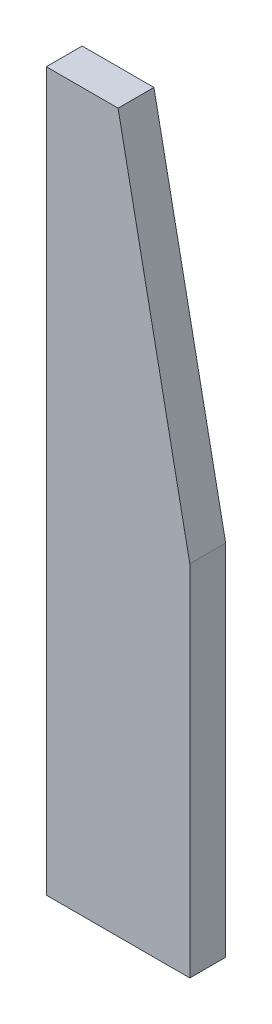
SolidWorks part; units mm, degrees
material "6061 Alloy"
ref_plane "Front Plane" through (0, 0, 0) normal (0, 0, 1) x (1, 0, 0)
ref_plane "Top Plane" through (0, 0, 0) normal (0, 1, 0) x (1, 0, 0)
ref_plane "Right Plane" through (0, 0, 0) normal (1, 0, 0) x (0, 0, -1)
sketch "Sketch1" plane through (0, 0, 0) normal (1, 0, 0) x (0, 0, -1)
  line L1 (-3.175, -63.5) -> (3.175, -63.5)
  line L2 (-3.175, -63.5) -> (-3.175, 63.5)
  line L3 (-3.175, 63.5) -> (3.175, 63.5)
  line L4 (3.175, -63.5) -> (3.175, 63.5)
  line L5 (-3.175, -63.5) -> (3.175, 63.5) construction
  line L6 (-3.175, 63.5) -> (3.175, -63.5) construction
  point P0 (0, 0)
  dimension "D1" = 6.35
  dimension "D2" = 127
extrude "Boss-Extrude1" add sketch "Sketch1" along normal blind 25.4
hole_wizard "M2.5x0.45 Tapped Hole1" positions "Sketch2" profile "Sketch3" tap size "M2.5x0.45" standard "ANSI Metric"
sketch "Sketch2" plane through (0, 0, 0) normal (-1, 0, 0) x (0, 0, 1)
  line L0 (0, -53.5) -> (0, -26.75)
  line L1 (0, -26.75) -> (0, 0)
  line L2 (0, 0) -> (0, 26.75)
  line L3 (0, 26.75) -> (0, 53.5)
  line L5 (-3.175, 63.5) -> (3.175, 63.5) construction
  point P0 (0, 53.5)
  point P2 (0, 26.75)
  point P4 (0, 0)
  point P7 (0, -26.75)
  point P9 (0, -53.5)
  dimension "D1" = 10
sketch "Sketch3" plane through (0, 53.5, 0) normal (0, 1, 0) x (0, 0, 1)
  line L0 (0, 0) -> (0, 6.9659)
  line L1 (0, 6.9659) -> (1.025, 6.35)
  line L2 (1.025, 6.35) -> (1.025, 0)
  line L5 (1.025, 0) -> (0, 0)
  line L10 (0, 6.9659) -> (-1.025, 6.35) construction
  line L11 (0, -6.35) -> (0, 107.95) construction
  dimension "Tap Drill Dia." = 2.05
  dimension "Tap Drill Depth" = 6.35
  dimension "Drill Angle" = 118
cosmetic thread "Hole Thread1" parameters "D1"=5, "D2"=2.5
cosmetic thread "Hole Thread2" parameters "D1"=5, "D2"=2.5
cosmetic thread "Hole Thread3" parameters "D1"=5, "D2"=2.5
cosmetic thread "Hole Thread4" parameters "D1"=5, "D2"=2.5
cosmetic thread "Hole Thread5" parameters "D1"=5, "D2"=2.5
sketch "Sketch4" plane through (0, 0, 3.175) normal (0, 0, 1) x (1, 0, 0)
  line L0 (12.7, 63.5) -> (25.4, 0)
  line L1 (25.4, 63.5) -> (0, 63.5) construction
  line L2 (25.4, 63.5) -> (25.4, -63.5) construction
  line M3 (25.4, -63.5) -> (25.4, 63.5)
  line M4 (25.4, 63.5) -> (0, 63.5)
extrude "Cut-Extrude1" cut sketch "Sketch4" against normal through all and the other way through all contours L0 M4 M3
